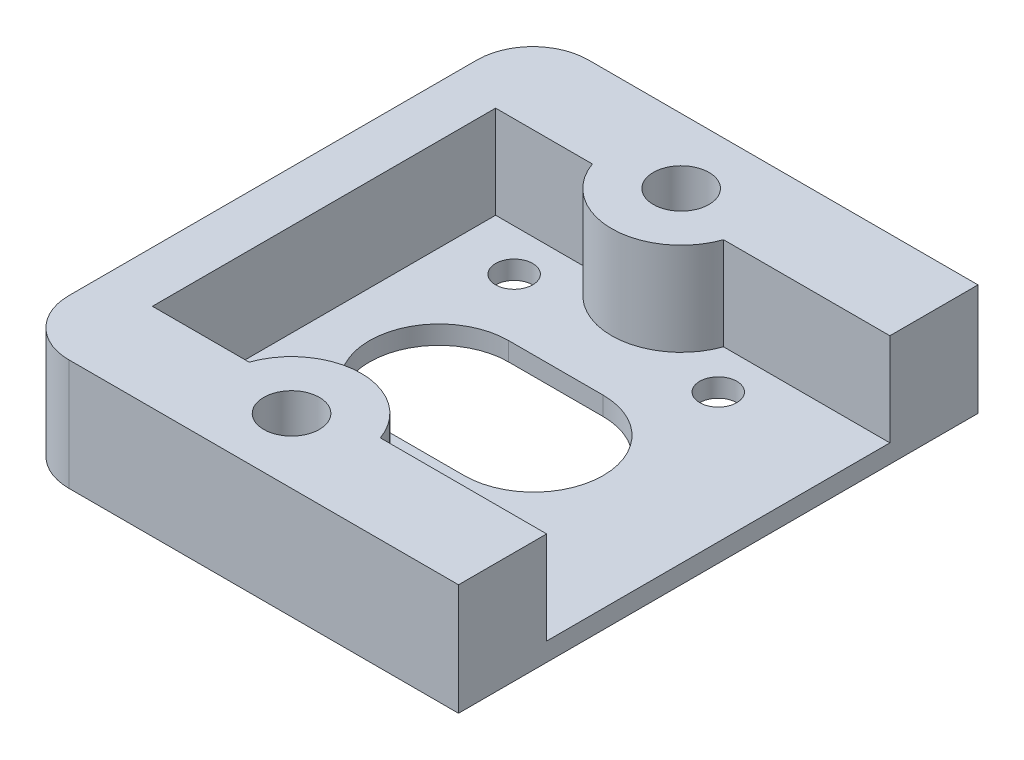
SolidWorks part; units mm, degrees
ref_plane "前视基准面" through (0, 0, 0) normal (0, 0, 1) x (1, 0, 0)
ref_plane "上视基准面" through (0, 0, 0) normal (0, 1, 0) x (1, 0, 0)
ref_plane "右视基准面" through (0, 0, 0) normal (1, 0, 0) x (0, 0, -1)
other "Configuration Table"
sketch "草图1" plane through (0, 0, 0) normal (0, 1, 0) x (1, 0, 0)
  line L1 (0, 0) -> (24, 0)
  line L2 (0, 0) -> (0, -28)
  line L3 (0, -28) -> (24, -28)
  line L4 (24, 0) -> (24, -28)
  dimension "D1" = 24
  dimension "D2" = 28
extrude "凸台-拉伸1" add sketch "草图1" along normal blind 6
sketch "草图2" plane through (0, 6, 0) normal (0, 1, 0) x (1, 0, 0)
  line L9 (0, 0) -> (0, -28) construction
  line L10 (2.75, -4.75) -> (20.25, -4.75)
  line L11 (0, -28) -> (24, -28) construction
  line L12 (2.75, -4.75) -> (2.75, -23.25)
  line L13 (2.75, -23.25) -> (20.25, -23.25)
  line L14 (20.25, -4.75) -> (20.25, -23.25)
  dimension "D1" = 18.5
  dimension "D2" = 17.5
  dimension "D3" = 2.75
  dimension "D4" = 4.75
extrude "切除-拉伸3" cut sketch "草图2" against normal blind 5
sketch "草图4" plane through (0, 1, 0) normal (0, 1, 0) x (1, 0, 0)
  line L0 (2.75, -14) -> (20.25, -14) construction
  line L1 (2.75, -4.75) -> (2.75, -23.25) construction
  line L2 (20.25, -23.25) -> (20.25, -4.75) construction
  line L3 (11.5, -4.75) -> (11.5, -23.25) construction
  line L4 (20.25, -4.75) -> (2.75, -4.75) construction
  line L5 (2.75, -23.25) -> (20.25, -23.25) construction
  line L6 (8.95, -14) -> (14.05, -14) construction
  line L7 (8.95, -10.25) -> (14.05, -10.25)
  line L8 (8.95, -17.75) -> (14.05, -17.75)
  arc A0 (8.95, -10.25) -> (8.95, -17.75) centre (8.95, -14) ccw
  arc A1 (14.05, -17.75) -> (14.05, -10.25) centre (14.05, -14) ccw
  circle A7 centre (6, -7) radius 1
  circle A12 centre (17, -7) radius 1
  circle A13 centre (6, -21) radius 1
  circle A14 centre (17, -21) radius 1
  point P14 (11.5, -14)
  dimension "D2" = 5.1
  dimension "D3" = 7
  dimension "D1" = 7.5
  dimension "D4" = 5.5
extrude "切除-拉伸4" cut sketch "草图4" against normal blind 5
sketch "草图5" plane through (0, 6, 0) normal (0, 1, 0) x (1, 0, 0)
  line L0 (24, -28) -> (24, 0) construction
  line L1 (20.25, -4.75) -> (24, -4.75)
  line L2 (20.25, -4.75) -> (20.25, -23.25)
  line L3 (20.25, -23.25) -> (24, -23.25)
  line L4 (24, -4.75) -> (24, -23.25)
  line L5 (2.75, -23.25) -> (20.25, -23.25) construction
extrude "切除-拉伸5" cut sketch "草图5" against normal blind 5
sketch "草图7" plane through (0, 6, 0) normal (0, 1, 0) x (1, 0, 0)
  line L1 (24, 0) -> (0, 0) construction
  line L3 (0, -14) -> (26.661, -14) construction
  line L4 (0, 0) -> (0, -28) construction
  line L5 (12.8463, 0) -> (10.1537, 0)
  line L6 (12.8463, -28) -> (10.1537, -28)
  line L7 (0, -28) -> (24, -28) construction
  circle A2 centre (11.5, -3.5) radius 1.5
  arc A5 (10.1537, 0) -> (12.8463, 0) centre (11.5, -3.5) ccw
  arc A6 (10.1537, -28) -> (12.8463, -28) centre (11.5, -24.5) cw
  circle A7 centre (11.5, -24.5) radius 1.5
  dimension "D1" = 3
  dimension "D3" = 3
  dimension "D4" = 7.5
  dimension "D5" = 11.5
  dimension "D2" = 21
fillet "圆角1" radius 3 2 edges at (0, 3, 0) (0, 3, 28)
extrude "凸台-拉伸4" add sketch "草图7" against normal blind 6
sketch "草图12" plane through (0, 6, 0) normal (0, 1, 0) x (1, 0, 0)
  circle A0 centre (11.5, -3.5) radius 1.5
  circle A1 centre (11.5, -24.5) radius 1.5
  dimension "D1" = 3
  dimension "D2" = 3
extrude "切除-拉伸6" cut sketch "草图12" against normal blind 10
